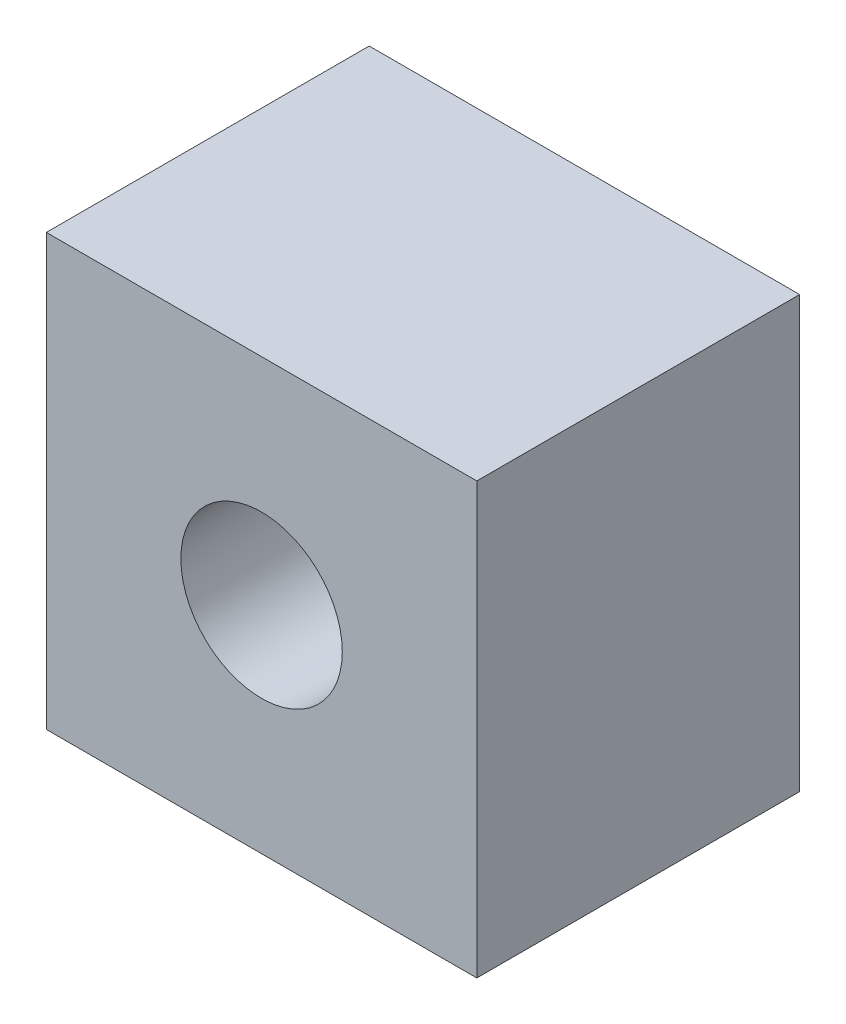
SolidWorks part; units mm, degrees
ref_plane "Plan de face" through (0, 0, 0) normal (0, 0, 1) x (1, 0, 0)
ref_plane "Plan de dessus" through (0, 0, 0) normal (0, 1, 0) x (1, 0, 0)
ref_plane "Plan de droite" through (0, 0, 0) normal (1, 0, 0) x (0, 0, -1)
sketch "Esquisse1" plane through (0, 0, 0) normal (0, 0, 1) x (1, 0, 0)
  line L1 (0, 0) -> (40, 0)
  line L2 (0, 0) -> (0, -40)
  line L3 (0, -40) -> (40, -40)
  line L4 (40, 0) -> (40, -40)
extrude "Boss.-Extru.1" add sketch "Esquisse1" along normal blind 30
hole_wizard "Dégagement M21" positions "Esquisse3D3" profile "Esquisse6" hole size "M2" standard "ISO" end condition through all
sketch3d "Esquisse3D3"
  point P0 (20, -20, 30)
sketch "Esquisse6" plane through (20, -20, 30) normal (1, 0, 0) x (0, -1, 0)
  line L0 (0, 0) -> (0, 30)
  line L1 (0, 30) -> (7.5, 30)
  line L2 (7.5, 30) -> (7.5, 0)
  line L5 (7.5, 0) -> (0, 0)
  line L11 (0, -6.35) -> (0, 107.95) construction
  dimension "Diamètre du perçage jusqu'au prochain" = 15
  dimension "Profondeur du perçage jusqu'au prochain" = 30
